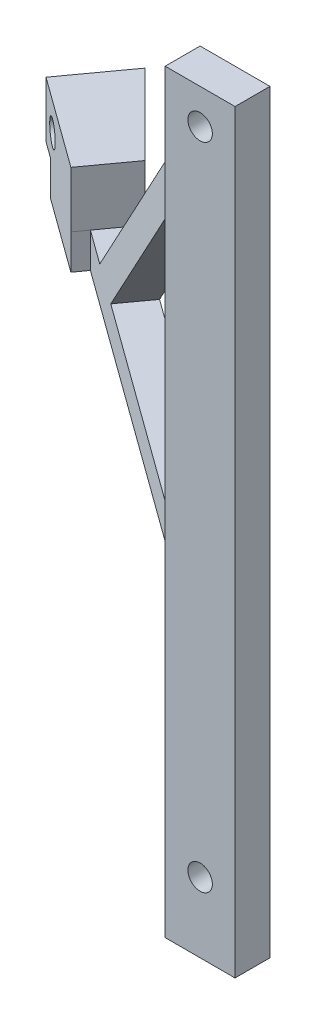
SolidWorks part; units mm, degrees
ref_plane "Front Plane" through (0, 0, 0) normal (0, 0, 1) x (1, 0, 0)
ref_plane "Top Plane" through (0, 0, 0) normal (0, 1, 0) x (1, 0, 0)
ref_plane "Right Plane" through (0, 0, 0) normal (1, 0, 0) x (0, 0, -1)
sketch "Sketch1" plane through (0, 0, 0) normal (0, 0, 1) x (1, 0, 0)
  line L0 (5, 0) -> (-5, 0)
  line L1 (-5, 0) -> (-5, 108)
  line L6 (-5, 108) -> (5, 108)
  line L7 (5, 108) -> (5, 0)
  point P8 (0, 0)
  dimension "D1" = 10
  dimension "D2" = 108
extrude "Boss-Extrude1" add sketch "Sketch1" along normal blind 5
sketch "Sketch2" plane through (0, 0, 5) normal (0, 0, 1) x (1, 0, 0)
  line L0 (-5, 0) -> (5, 0) construction
  line L1 (5, 108) -> (-5, 108) construction
  circle A0 centre (0, 10) radius 1.75
  circle A1 centre (0, 103) radius 1.75
  dimension "D1" = 3.5
  dimension "D2" = 3.5
  dimension "D3" = 10
  dimension "D4" = 5
extrude "Cut-Extrude1" cut sketch "Sketch2" against normal through all
ref_plane "Plane2" through (0, 49.1, 0) normal (0, -1, 0) x (-1, 0, 0)
sketch "Sketch4" plane through (0, 49.1, 0) normal (0, -1, 0) x (-1, 0, 0)
  line L0 (3.3778, 0) -> (40.9973, 27.282)
  line L1 (5, 0) -> (-5, 0) construction
  line L2 (5, 0) -> (5, 29.25) construction
  line L3 (5, 29.25) -> (47.97, 29.25) construction
  line L5 (43.9326, 23.2343) -> (5, -5)
  line L6 (5, -5) -> (3.3778, 0)
  line L7 (4.1889, -2.5) -> (52.9891, 32.8899) construction
  line L8 (5, -5) -> (5, 0) construction
  line L9 (40.9973, 27.282) -> (40.7037, 27.6868)
  line L10 (40.7037, 27.6868) -> (51.2276, 35.3188)
  line L11 (51.2276, 35.3188) -> (55.6307, 29.2473)
  line L12 (43.9326, 23.2343) -> (45.1068, 21.6153)
  line L13 (45.1068, 21.6153) -> (55.6307, 29.2473)
  line L14 (40.9973, 27.282) -> (43.9326, 23.2343) construction
  circle A1 centre (47.97, 29.25) radius 2.2 construction
  dimension "D3" = 4.4
  dimension "D5" = 6.2
  dimension "D1" = 29.25
  dimension "D2" = 42.97
  dimension "D4" = 2
  dimension "D6" = 5
  dimension "D7" = 13
  dimension "D8" = 144.05
  dimension "D9" = 0.5
extrude "Boss-Extrude2" add sketch "Sketch4" against normal blind 5 contours L5 L6 L0 L9 L10 L11 L13 L12
sketch "Sketch5" plane through (0, 49.1, 0) normal (0, -1, 0) x (1, 0, 0)
  circle A0 centre (-47.97, -29.25) radius 2.2
  dimension "D1" = 4.4
extrude "Cut-Extrude2" cut sketch "Sketch5" against normal up to surface (5 mm away) up to face at (-32.3307, 54.1, -17.7094)
sketch "Sketch6" plane through (-4.0996, 0, 5.653) normal (-0.5871, 0, 0.8095) x (0.8095, 0, 0.5871)
  line L0 (-43.1833, 54.1) -> (-1.1123, 96.1711)
  line L1 (-49.2052, 54.1) -> (-1.1123, 54.1) construction
  line L2 (-1.1123, 108) -> (-1.1123, 54.1) construction
  line L3 (-1.1123, 96.1711) -> (-1.1123, 89.1)
  line L4 (-1.1123, 89.1) -> (-36.1123, 54.1)
  line L5 (-36.1123, 54.1) -> (-43.1833, 54.1)
  dimension "D1" = 5
  dimension "D2" = 45
  dimension "D3" = 35
extrude "Boss-Extrude3" add sketch "Sketch6" against normal up to surface (5 mm away) up to face at (-22.1875, 51.6, -13.641)
sketch "Sketch7" plane through (0, 54.1, 0) normal (0, 1, 0) x (1, 0, 0)
  line L0 (-40.645, 27.7677) -> (-52.103, 39.2218)
  line L1 (-52.103, 39.2218) -> (-58.0593, 31.0086)
  line L2 (-58.0593, 31.0086) -> (-45.1068, 21.6153)
  line L3 (-45.1068, 21.6153) -> (-40.645, 27.7677)
  line L4 (-40.9973, 27.282) -> (-40.7037, 27.6868) construction
  line L5 (-40.7037, 27.6868) -> (-51.2276, 35.3188) construction
  line L6 (-51.2276, 35.3188) -> (-55.6307, 29.2473) construction
  dimension "D1" = 9.04
  dimension "D2" = 3
  dimension "D3" = 0.1
extrude "Boss-Extrude4" add sketch "Sketch7" along normal blind 8
sketch "Sketch8" plane through (-6.4318, 0, 6.434) normal (0.707, 0, -0.7072) x (-0.7072, 0, -0.707)
  line L0 (48.3766, 62.1) -> (48.3766, 54.1) construction
  circle A0 centre (58.8766, 58.1) radius 1.75
  point P4 (48.3766, 58.1)
  dimension "D1" = 3.5
  dimension "D2" = 10.5
extrude "Cut-Extrude3" cut sketch "Sketch8" against normal through all
